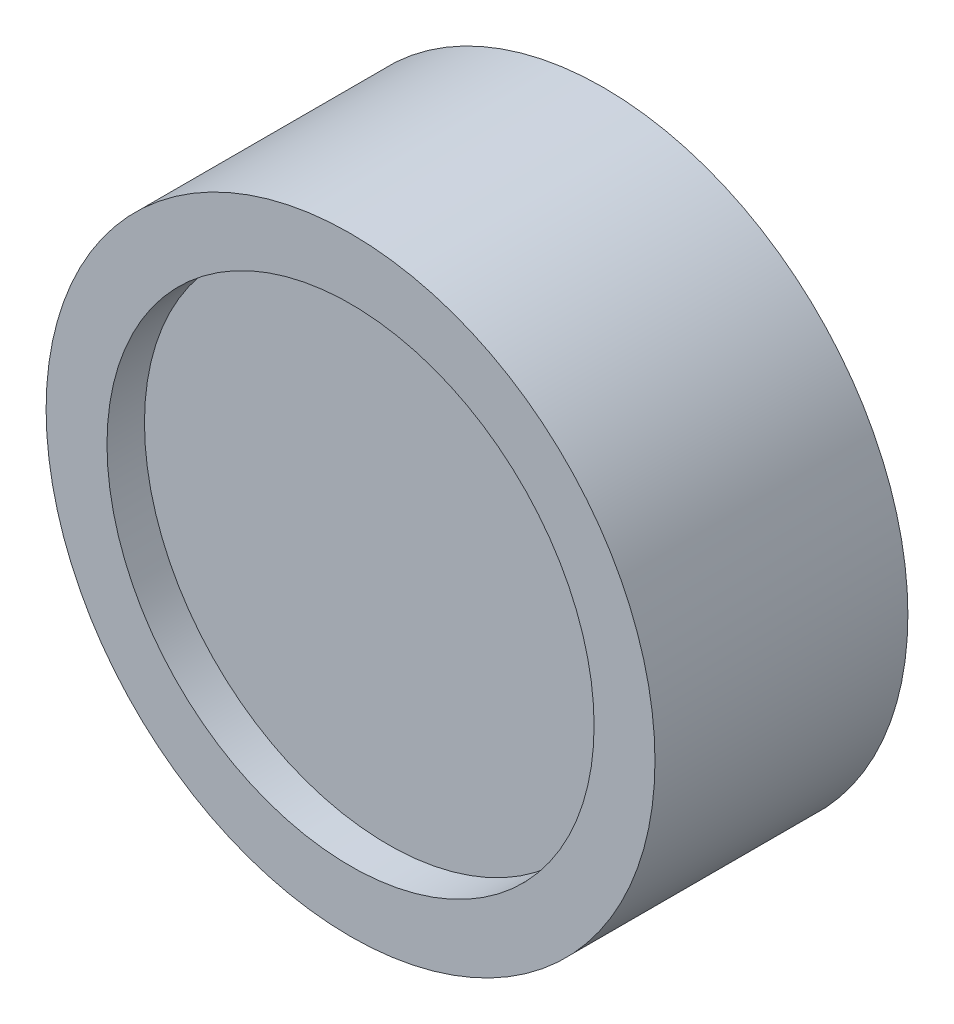
SolidWorks part; units mm, degrees
ref_plane "前视基准面" through (0, 0, 0) normal (0, 0, 1) x (1, 0, 0)
ref_plane "上视基准面" through (0, 0, 0) normal (0, 1, 0) x (1, 0, 0)
ref_plane "右视基准面" through (0, 0, 0) normal (1, 0, 0) x (0, 0, -1)
sketch "草图1" plane through (0, 0, 0) normal (0, 0, 1) x (1, 0, 0)
  circle A0 centre (0, 0) radius 32.5
extrude "凸台-拉伸1" add sketch "草图1" along normal blind 20 and the other way blind 7 contours A0
sketch "草图2" plane through (0, 0, 0) normal (0, 0, 1) x (1, 0, 0)
  circle A1 centre (0, 0) radius 26
sketch "草图3" plane through (0, 0, 0) normal (0, 0, 1) x (1, 0, 0)
  line L2 (10, 0) -> (20, 0)
  line L3 (8.6603, 5) -> (17.3205, 10)
  line L4 (-5, 8.6603) -> (-10, 17.3205)
  line L5 (-5, -8.6603) -> (-10, -17.3205)
  line L6 (-8.6603, 5) -> (-17.3205, 10)
  line L7 (0, -10) -> (0, -20)
  circle A0 centre (0, 0) radius 26
  arc A1 (-8.6603, 5) -> (-5, -8.6603) centre (0, 0) ccw
  arc A2 (0, -20) -> (20, 0) centre (0, 0) ccw
  arc A3 (8.6603, 5) -> (-5, 8.6603) centre (0, 0) ccw
  arc A4 (0, -10) -> (10, 0) centre (0, 0) ccw
  arc A5 (17.3205, 10) -> (-10, 17.3205) centre (0, 0) ccw
  arc A6 (-17.3205, 10) -> (-10, -17.3205) centre (0, 0) ccw
extrude "切除-拉伸6" cut sketch "草图2" along normal blind 55 and the other way blind 81 contours A1
extrude "凸台-拉伸4" add sketch "草图3" along normal blind 16 and the other way blind 3 contours A0
